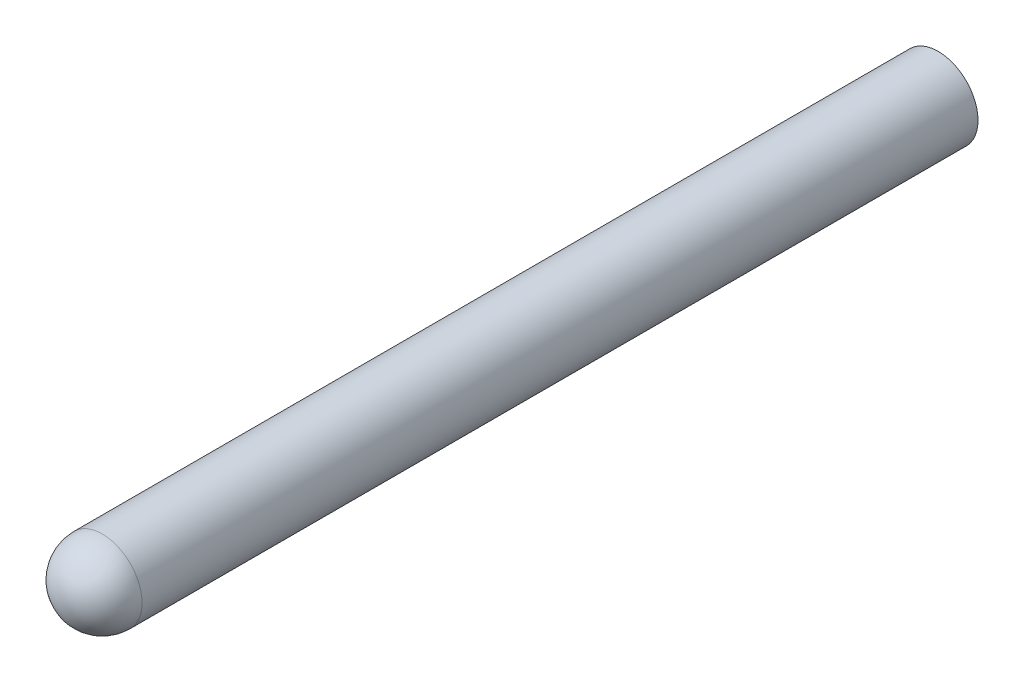
SolidWorks part; units mm, degrees
material "Plain Carbon Steel"
ref_plane "Front Plane" through (0, 0, 0) normal (0, 0, 1) x (1, 0, 0)
ref_plane "Top Plane" through (0, 0, 0) normal (0, 1, 0) x (1, 0, 0)
ref_plane "Right Plane" through (0, 0, 0) normal (1, 0, 0) x (0, 0, -1)
sketch "Sketch1" plane through (0, 0, 0) normal (0, 0, 1) x (1, 0, 0)
  circle A0 centre (0, 0) radius 12.7
  circle A1 centre (0, 0) radius 8.89
  dimension "D1" = 25.4
  dimension "D2" = 3.81
extrude "Boss-Extrude1" add sketch "Sketch1" along normal blind 266.7
sketch "Sketch2" plane through (0, 0, 0) normal (0, 1, 0) x (1, 0, 0)
  line L0 (-12.7, -266.7) -> (0, -266.7)
  line L1 (-12.7, -266.7) -> (12.7, -266.7) construction
  line L2 (0, -266.7) -> (0, -279.4)
  line L3 (0, -279.4) -> (0, -255.776) construction
  arc A0 (-12.7, -266.7) -> (0, -279.4) centre (0, -266.7) ccw
  dimension "D1" = 12.7
  dimension "D2" = 12.7
revolve "Revolve1" add sketch "Sketch2" angle 360 about L3
sketch "Sketch3" plane through (0, 0, 0) normal (0, 0, -1) x (-1, 0, 0)
  circle A0 centre (0, 0) radius 10.16
  circle A1 centre (0, 0) radius 12.7 construction
  dimension "D1" = 2.54
extrude "Cut-Extrude1" cut sketch "Sketch3" against normal blind 12.7
chamfer "Chamfer1" distance 1.27 angle 45 1 edges at (-10.16, 0, 0)
fillet "Fillet1" radius 0.635 1 edges at (-10.16, 0, 12.7)
